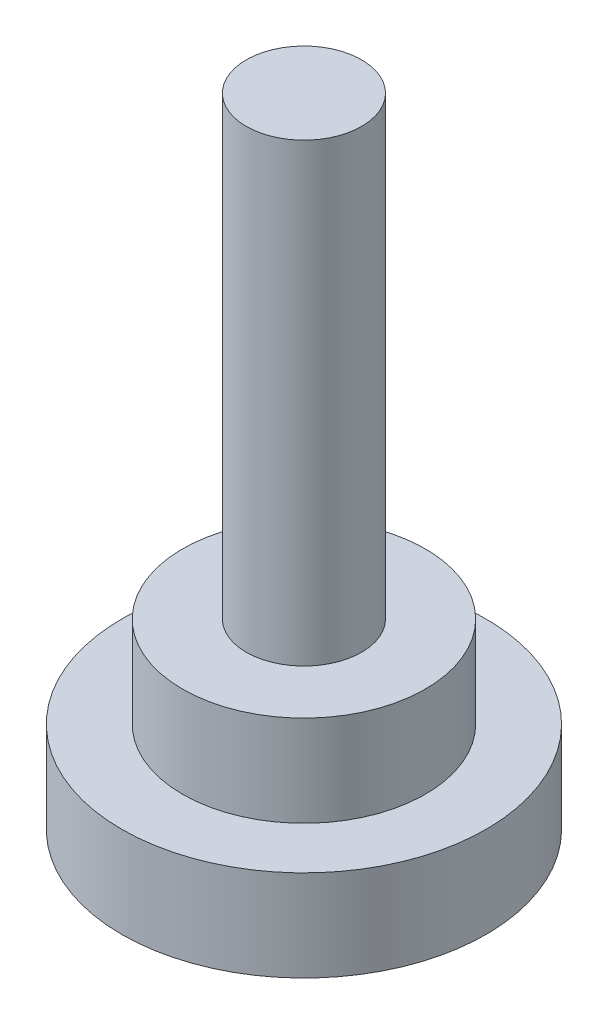
SolidWorks part; units mm, degrees
ref_plane "Front Plane" through (0, 0, 0) normal (0, 0, 1) x (1, 0, 0)
ref_plane "Top Plane" through (0, 0, 0) normal (0, 1, 0) x (1, 0, 0)
ref_plane "Right Plane" through (0, 0, 0) normal (1, 0, 0) x (0, 0, -1)
sketch "Sketch1" plane through (0, 0, 0) normal (0, 1, 0) x (1, 0, 0)
  circle A0 centre (0, 0) radius 6
  dimension "D1" = 12
extrude "Boss-Extrude1" add sketch "Sketch1" along normal blind 3
sketch "Sketch2" plane through (0, 3, 0) normal (0, 1, 0) x (1, 0, 0)
  circle A0 centre (0, 0) radius 1.9
  dimension "D1" = 3.8
extrude "Boss-Extrude2" add sketch "Sketch2" along normal blind 18
sketch "Sketch4" plane through (0, 3, 0) normal (0, 1, 0) x (1, 0, 0)
  circle A0 centre (0, 0) radius 4
  dimension "D1" = 8
extrude "Boss-Extrude3" add sketch "Sketch4" along normal blind 3
